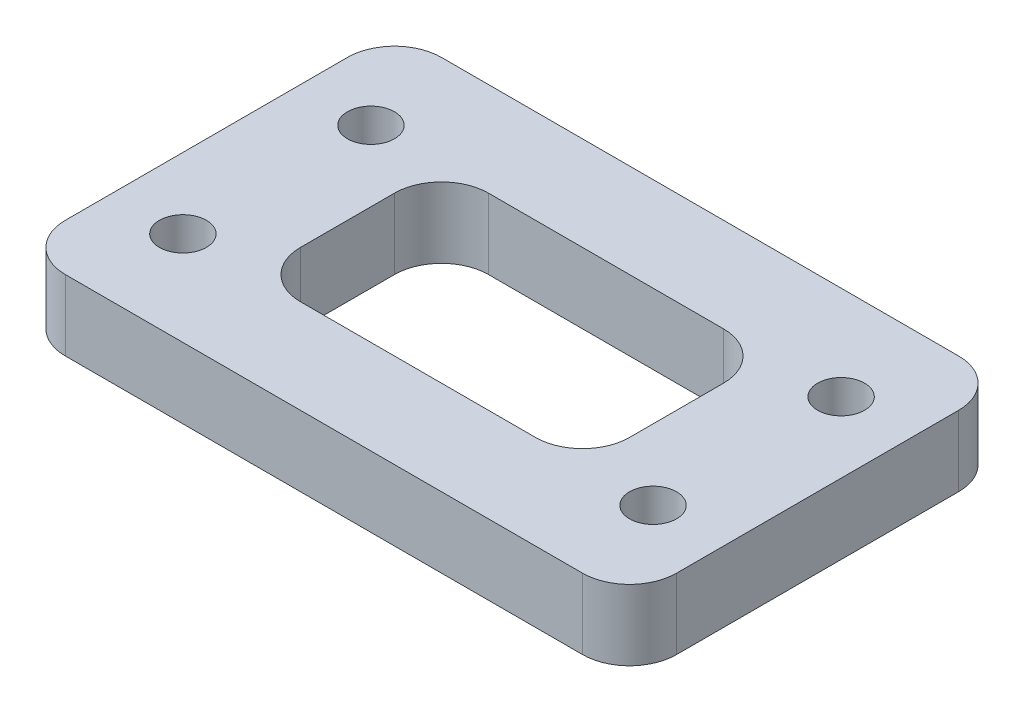
SolidWorks part; units mm, degrees
ref_plane "Front Plane" through (0, 0, 0) normal (0, 0, 1) x (1, 0, 0)
ref_plane "Top Plane" through (0, 0, 0) normal (0, 1, 0) x (1, 0, 0)
ref_plane "Right Plane" through (0, 0, 0) normal (1, 0, 0) x (0, 0, -1)
sketch "Sketch1" plane through (0, 0, 0) normal (0, 1, 0) x (1, 0, 0)
  line L0 (-32.5, 0) -> (-38.5253, 0) construction
  line L1 (27.5, 20) -> (-27.5, 20)
  line L2 (32.5, 15) -> (32.5, -15)
  line L3 (27.5, -20) -> (-27.5, -20)
  line L4 (-32.5, 15) -> (-32.5, -15)
  line L5 (32.5, 20) -> (-32.5, -20) construction
  line L6 (32.5, -20) -> (-32.5, 20) construction
  line L8 (12.5, 10) -> (-12.5, 10)
  line L9 (17.5, 5) -> (17.5, -5)
  line L10 (12.5, -10) -> (-12.5, -10)
  line L11 (-17.5, 5) -> (-17.5, -5)
  line L12 (17.5, 10) -> (-17.5, -10) construction
  line L13 (17.5, -10) -> (-17.5, 10) construction
  circle A0 centre (-25, 10) radius 2.5
  circle A1 centre (25, 10) radius 2.5
  circle A2 centre (25, -10) radius 2.5
  circle A3 centre (-25, -10) radius 2.5
  arc A4 (-17.5, 5) -> (-12.5, 10) centre (-12.5, 5) cw
  arc A5 (17.5, 5) -> (12.5, 10) centre (12.5, 5) ccw
  arc A6 (12.5, -10) -> (17.5, -5) centre (12.5, -5) ccw
  arc A7 (-12.5, -10) -> (-17.5, -5) centre (-12.5, -5) cw
  arc A8 (32.5, 15) -> (27.5, 20) centre (27.5, 15) ccw
  arc A9 (27.5, -20) -> (32.5, -15) centre (27.5, -15) ccw
  arc A10 (-32.5, -15) -> (-27.5, -20) centre (-27.5, -15) ccw
  arc A11 (-32.5, 15) -> (-27.5, 20) centre (-27.5, 15) cw
  point P0 (0, 0)
  point P16 (0, 0)
  dimension "D1" = 50
  dimension "D2" = 7.5
  dimension "D5" = 5
  dimension "D6" = 5
  dimension "D3" = 10
  dimension "D4" = 10
extrude "Boss-Extrude1" add sketch "Sketch1" along normal blind 7.5
